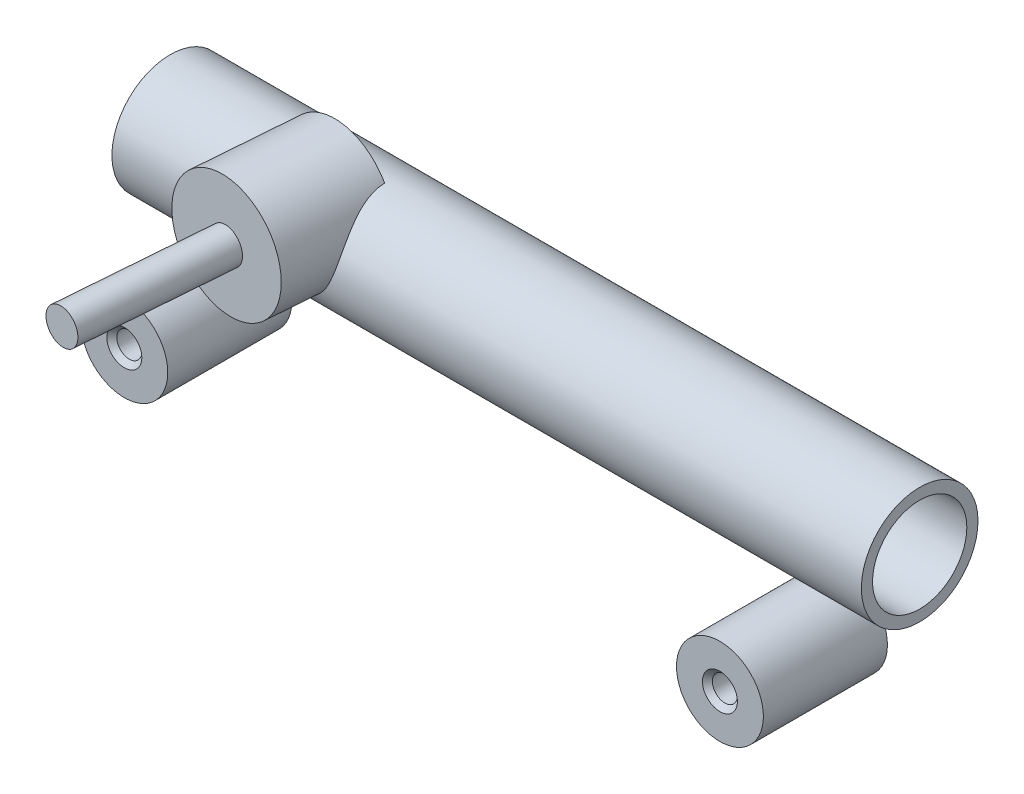
SolidWorks part; units mm, degrees
ref_plane "Płaszczyzna przednia" through (0, 0, 0) normal (0, 0, 1) x (1, 0, 0)
ref_plane "Płaszczyzna górna" through (0, 0, 0) normal (0, 1, 0) x (1, 0, 0)
ref_plane "Płaszczyzna prawa" through (0, 0, 0) normal (1, 0, 0) x (0, 0, -1)
sketch "Szkic1" plane through (0, 0, 0) normal (1, 0, 0) x (0, 0, -1)
  circle A0 centre (0, 0) radius 23.5
  dimension "D1" = 47
extrude "Dodanie-wyciągnięcie1" add sketch "Szkic1" along normal blind 302
ref_plane "Płaszczyzna1" through (0, 23.5, 0) normal (0, 1, 0) x (1, 0, 0)
sketch "Szkic3" plane through (0, 23.5, 0) normal (0, 1, 0) x (1, 0, 0)
  line L0 (0, 0) -> (302, 0) construction
  line L1 (302, -23.5) -> (302, 23.5) construction
  point P3 (0, 0)
sketch "Szkic2" plane through (0, 0, 0) normal (0, 0, 1) x (1, 0, 0)
  line L0 (0, 23.5) -> (0, -23.5) construction
  line L1 (302, 23.5) -> (0, 23.5) construction
  circle A0 centre (31.5, -38) radius 17.5
  dimension "D1" = 35
  dimension "D2" = 31.5
  dimension "D3" = 61.5
extrude "Dodanie-wyciągnięcie2" add sketch "Szkic2" along normal blind 50
sketch "Szkic4" plane through (0, 0, 0) normal (0, 0, -1) x (-1, 0, 0)
  line L0 (-31.5, -38) -> (-323.956, -38) construction
  circle A0 centre (-271.5, -38) radius 17.5
  circle A1 centre (-31.5, -38) radius 17.5 construction
  dimension "D1" = 240
  dimension "D2" = 35
extrude "Dodanie-wyciągnięcie3" add sketch "Szkic4" against normal blind 50
sketch "Szkic5" plane through (0, 0, 50) normal (0, 0, 1) x (1, 0, 0)
  circle A0 centre (31.5, -38) radius 5.05
  circle A1 centre (271.5, -38) radius 5.05
  dimension "D1" = 10.1
  dimension "D2" = 10.1
extrude "Wytnij-wyciągnięcie1" cut sketch "Szkic5" against normal blind 50
chamfer "Sfazowanie1" distance 2 angle 45 4 edges at (36.55, -38, 0) (276.55, -38, 0) (276.55, -38, 50) (36.55, -38, 50)
sketch "Szkic7" plane through (0, 23.5, 0) normal (0, 1, 0) x (1, 0, 0)
  line L0 (68, 0) -> (64.6945, -42) construction
  line L1 (0, 0) -> (302, 0) construction
  line L2 (0, 23.5) -> (0, -23.5) construction
  line L3 (68, 0) -> (68, -42) construction
  point P6 (63.7208, -54.3732)
  point P8 (0, 0)
  dimension "D1" = 68
  dimension "D2" = 4.5
  dimension "D3" = 42
ref_plane "Płaszczyzna2" through (0, -55.5, 0) normal (0, -1, 0) x (-1, 0, 0)
ref_plane "Płaszczyzna3" through (64.6945, 23.5, 42) normal (-0.0785, 0, 0.9969) x (0.9969, 0, 0.0785)
sketch "Szkic8" plane through (64.6945, 23.5, 42) normal (-0.0785, 0, 0.9969) x (0.9969, 0, 0.0785)
  line L0 (0, 0) -> (0, -79) construction
  line L1 (-95.2904, -79) -> (-40.2904, -79) construction
  circle A0 centre (0, -13.25) radius 24
  dimension "D2" = 48
  dimension "D1" = 65.75
extrude "Dodanie-wyciągnięcie4" add sketch "Szkic8" against normal up to vertex (42.1299 mm away) up to point (68, 23.5, 0)
sketch "Szkic10" plane through (0, 0, 0) normal (-1, 0, 0) x (0, 0, 1)
  line L0 (23.5, 0) -> (103.5, 0) construction
  circle A0 centre (0, 0) radius 23.5 construction
  dimension "D1" = 80
sketch "Szkic11" plane through (0, 23.5, 0) normal (0, 1, 0) x (1, 0, 0)
  line L0 (64.6945, -42) -> (59.8544, -103.5) construction
  line L1 (68, 0) -> (64.6945, -42) construction
  point P5 (0, 0)
  dimension "D1" = 61.6902
sketch "Szkic12" plane through (-2.8869, 0, 36.6812) normal (-0.0785, 0, 0.9969) x (0.9969, 0, 0.0785)
  circle A0 centre (67.7904, 10.25) radius 7
  dimension "D1" = 14
extrude "Dodanie-wyciągnięcie5" add sketch "Szkic12" along normal up to vertex (61.6902 mm away) up to point (59.8544, 23.5, 103.5)
sketch "Szkic6" plane through (0, 0, 0) normal (-1, 0, 0) x (0, 0, 1)
  circle A0 centre (0, 0) radius 19
  dimension "D1" = 38
extrude "Wytnij-wyciągnięcie2" cut sketch "Szkic6" against normal up to surface (302 mm away) up to face at (302, 0, -23.5)
sketch "Szkic13" plane through (64.6945, 23.5, 42) normal (-0.0785, 0, 0.9969) x (0.9969, 0, 0.0785)
  circle A0 centre (0, -13.25) radius 7
extrude "Dodanie-wyciągnięcie6" add sketch "Szkic13" against normal blind 50
